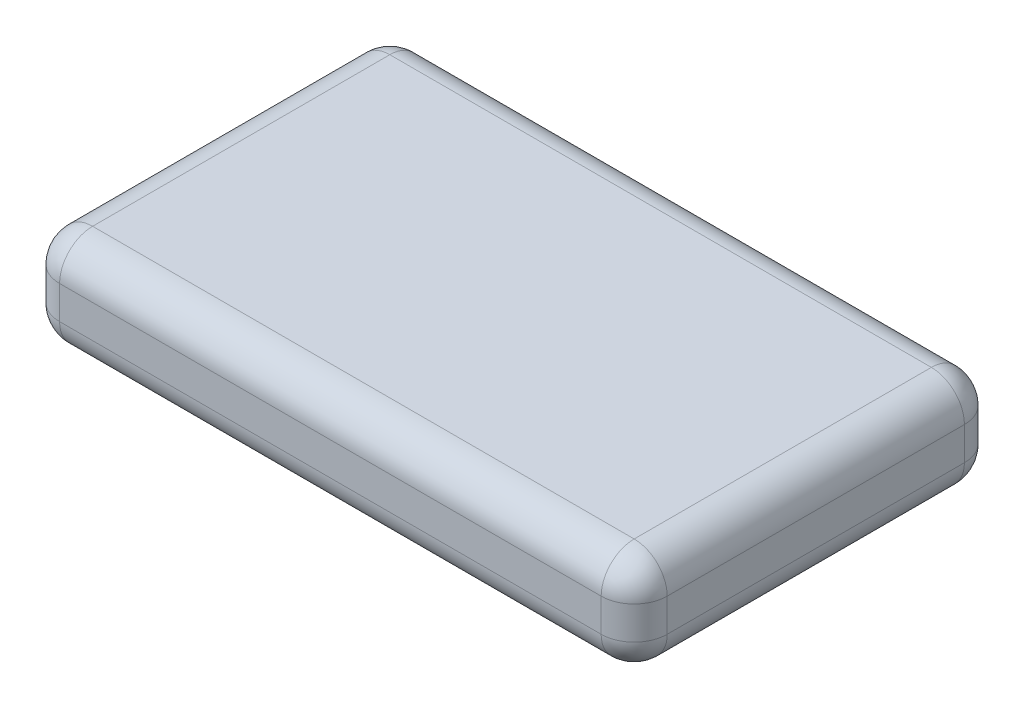
SolidWorks part; units mm, degrees
ref_plane "Front Plane" through (0, 0, 0) normal (0, 0, 1) x (1, 0, 0)
ref_plane "Top Plane" through (0, 0, 0) normal (0, 1, 0) x (1, 0, 0)
ref_plane "Right Plane" through (0, 0, 0) normal (1, 0, 0) x (0, 0, -1)
sketch "Sketch1" plane through (0, 0, 0) normal (0, 1, 0) x (1, 0, 0)
  line L1 (0, 0) -> (92, 0)
  line L2 (0, 0) -> (0, 55)
  line L3 (0, 55) -> (92, 55)
  line L4 (92, 0) -> (92, 55)
  dimension "D1" = 55
  dimension "D2" = 92
extrude "Boss-Extrude1" add sketch "Sketch1" along normal blind 15
fillet "Fillet3" radius 5 12 edges at (92, 7.5, 0) (92, 7.5, -55) (46, 0, 0) (92, 0, -27.5) (46, 0, -55) (0, 7.5, -55) (0, 7.5, 0) (0, 0, -27.5) (46, 15, -55) (92, 15, -27.5) (46, 15, 0) (0, 15, -27.5)
